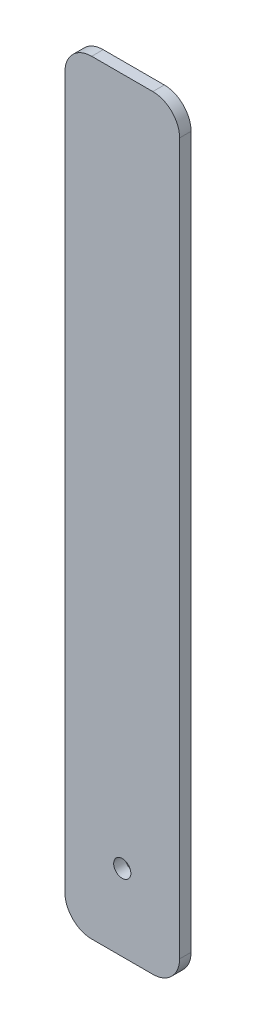
SolidWorks part; units mm, degrees
ref_plane "Front Plane" through (0, 0, 0) normal (0, 0, 1) x (1, 0, 0)
ref_plane "Top Plane" through (0, 0, 0) normal (0, 1, 0) x (1, 0, 0)
ref_plane "Right Plane" through (0, 0, 0) normal (1, 0, 0) x (0, 0, -1)
sketch "Sketch2" plane through (0, 0, 0) normal (0, 0, 1) x (1, 0, 0)
  line L1 (8, -100) -> (-8, -100)
  line L2 (15, -93) -> (15, 93)
  line L3 (8, 100) -> (-8, 100)
  line L4 (-15, -93) -> (-15, 93)
  line L5 (15, -100) -> (-15, 100) construction
  line L6 (15, 100) -> (-15, -100) construction
  arc A0 (15, -93) -> (8, -100) centre (8, -93) cw
  arc A1 (-8, -100) -> (-15, -93) centre (-8, -93) cw
  arc A2 (8, 100) -> (15, 93) centre (8, 93) cw
  arc A3 (-8, 100) -> (-15, 93) centre (-8, 93) ccw
  circle A4 centre (0, -80) radius 2.25
  point P0 (0, 0)
  dimension "D1" = 7
  dimension "D2" = 20
  dimension "D3" = 200
extrude "Boss-Extrude1" add sketch "Sketch2" along normal blind 3
